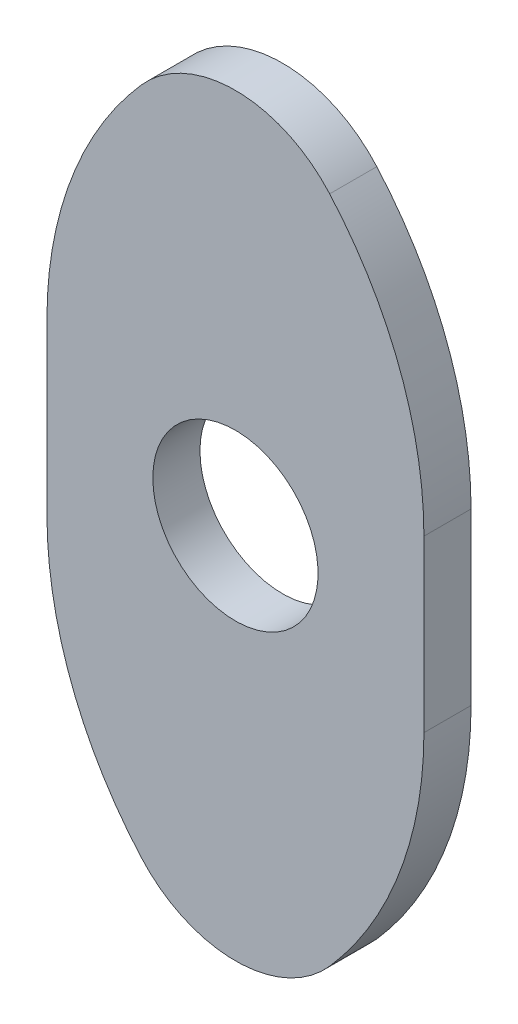
SolidWorks part; units mm, degrees
ref_plane "front" through (0, 0, 0) normal (0, 0, 1) x (1, 0, 0)
ref_plane "top" through (0, 0, 0) normal (0, 1, 0) x (1, 0, 0)
ref_plane "right" through (0, 0, 0) normal (1, 0, 0) x (0, 0, -1)
sketch "Sketch1" plane through (0, 0, 0) normal (0, 0, 1) x (1, 0, 0)
  line L0 (0, 25.4) -> (0, -25.4) construction
  line L1 (19.05, 8.5995) -> (19.05, -8.5995)
  line L2 (-19.05, 8.5995) -> (-19.05, -8.5995)
  line L3 (0, 0) -> (35.7663, 0) construction
  circle A4 centre (0, 0) radius 19.05 construction
  circle A5 centre (0, 0) radius 8.3503
  arc A6 (9.525, 33.8003) -> (-9.525, 33.8003) centre (0, 25.4) ccw
  arc A8 (19.05, 8.5995) -> (9.525, 33.8003) centre (-19.05, 8.5995) ccw
  arc A10 (-19.05, 8.5995) -> (-9.525, 33.8003) centre (19.05, 8.5995) cw
  arc A11 (-19.05, -8.5995) -> (-9.525, -33.8003) centre (19.05, -8.5995) ccw
  arc A12 (9.525, -33.8003) -> (-9.525, -33.8003) centre (0, -25.4) cw
  arc A13 (19.05, -8.5995) -> (9.525, -33.8003) centre (-19.05, -8.5995) cw
  dimension "D1" = 16.7005
  dimension "D2" = 25.4
  dimension "D3" = 38.1
  dimension "D5" = 38.1
  dimension "D4" = 50.8
extrude "Base-Extrude" add sketch "Sketch1" along normal blind 4.7625
